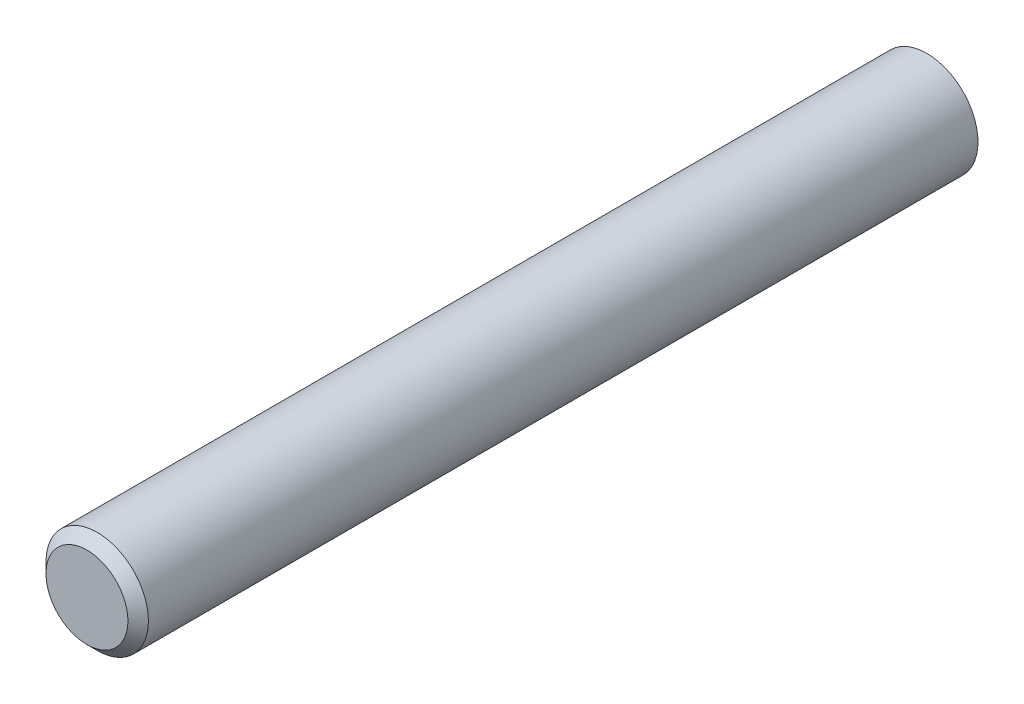
SolidWorks part; units mm, degrees
material "6061 Alloy"
ref_plane "Front Plane" through (0, 0, 0) normal (0, 0, 1) x (1, 0, 0)
ref_plane "Top Plane" through (0, 0, 0) normal (0, 1, 0) x (1, 0, 0)
ref_plane "Right Plane" through (0, 0, 0) normal (1, 0, 0) x (0, 0, -1)
sketch "Sketch1" plane through (0, 0, 0) normal (0, 0, 1) x (1, 0, 0)
  circle A0 centre (0, 0) radius 5
  dimension "D1" = 10
extrude "Boss-Extrude1" add sketch "Sketch1" along normal blind 82
chamfer "Chamfer1" distance 1 angle 45 1 edges at (5, 0, 82)
